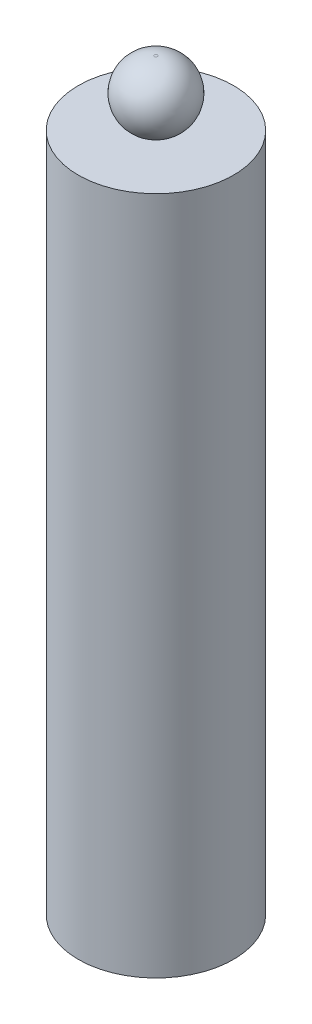
SolidWorks part; units mm, degrees
ref_plane "Front Plane" through (0, 0, 0) normal (0, 0, 1) x (1, 0, 0)
ref_plane "Top Plane" through (0, 0, 0) normal (0, 1, 0) x (1, 0, 0)
ref_plane "Right Plane" through (0, 0, 0) normal (1, 0, 0) x (0, 0, -1)
sketch "Sketch1" plane through (0, 0, 0) normal (0, 1, 0) x (1, 0, 0)
  circle A0 centre (0, 0) radius 24
  dimension "D1" = 48
extrude "Boss-Extrude1" add sketch "Sketch1" along normal blind 230
sketch "Sketch3" plane through (0, 0, 0) normal (0, 0, 1) x (1, 0, 0)
  line L2 (24, 230) -> (24, 210)
  line L3 (24, 0) -> (24, 230) construction
  line L7 (0, 241.4654) -> (0, 0) construction
  line L8 (24, 210) -> (0.5, 210)
  line L9 (24, 230) -> (0.5, 230)
  arc A0 (0.5, 210) -> (0.5, 230) centre (0.5, 220) ccw
  point P2 (0, 0)
  point P10 (0, 0)
  point P11 (0, 0)
  point P15 (0, 0)
  point P18 (0, 0)
  point P19 (0, 0)
  point P20 (0, 0)
  dimension "D2" = 10
  dimension "D1" = 20
  dimension "D3" = 23.5
revolve "Cut-Revolve2" cut sketch "Sketch3" angle 360 about L7
